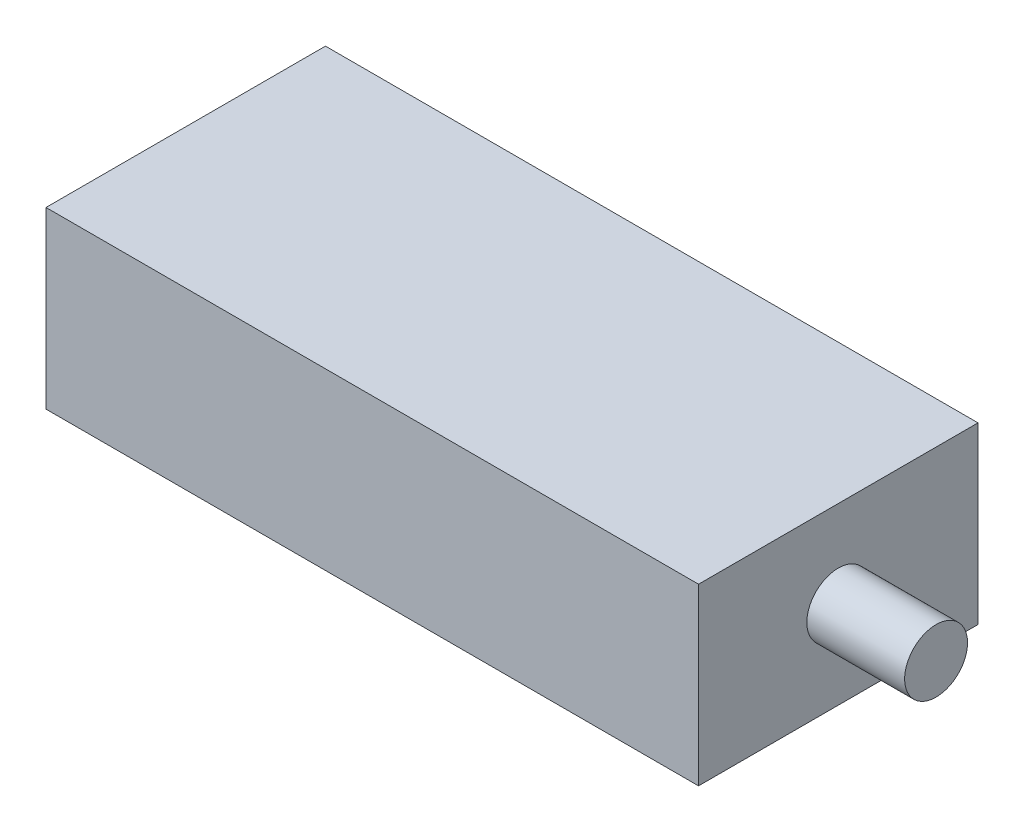
SolidWorks part; units mm, degrees
ref_plane "Front Plane" through (0, 0, 0) normal (0, 0, 1) x (1, 0, 0)
ref_plane "Top Plane" through (0, 0, 0) normal (0, 1, 0) x (1, 0, 0)
ref_plane "Right Plane" through (0, 0, 0) normal (1, 0, 0) x (0, 0, -1)
sketch "Sketch1" plane through (0, 0, 0) normal (0, 1, 0) x (1, 0, 0)
  line L1 (-59.309, -25.4) -> (59.309, -25.4)
  line L2 (-59.309, -25.4) -> (-59.309, 25.4)
  line L3 (-59.309, 25.4) -> (59.309, 25.4)
  line L4 (59.309, -25.4) -> (59.309, 25.4)
  line L5 (-59.309, -25.4) -> (59.309, 25.4) construction
  line L6 (-59.309, 25.4) -> (59.309, -25.4) construction
  point P0 (0, 0)
  dimension "D1" = 118.618
  dimension "D2" = 50.8
extrude "Boss-Extrude1" add sketch "Sketch1" along normal blind 31.75
sketch "Sketch2" plane through (59.309, 0, 0) normal (1, 0, 0) x (0, 0, -1)
  line L0 (-25.4, 31.75) -> (-25.4, 0) construction
  circle A0 centre (0, 15.875) radius 5.715
  point P10 (-25.4, 15.875)
  dimension "D1" = 11.43
extrude "Boss-Extrude2" add sketch "Sketch2" along normal blind 17.78
sketch "Sketch3" plane through (-59.309, 0, 0) normal (-1, 0, 0) x (0, 0, 1)
  line L1 (-7.964, 11.6586) -> (-2.54, 11.6586)
  line L3 (-7.964, 20.0914) -> (-2.54, 20.0914)
  line L5 (-2.54, 11.6586) -> (0, 14.1986)
  line L6 (0, 14.1986) -> (0, 11.6586) construction
  line L8 (-2.54, 20.0914) -> (0, 17.5514)
  line L9 (0, 17.5514) -> (0, 20.0914) construction
  line L11 (0, 0) -> (0, 41.1546) construction
  line L14 (2.54, 20.0914) -> (0, 17.5514)
  line L15 (2.54, 11.6586) -> (0, 14.1986)
  line L16 (7.964, 20.0914) -> (2.54, 20.0914)
  line L18 (7.964, 11.6586) -> (2.54, 11.6586)
  arc A0 (-7.964, 11.6586) -> (-7.964, 20.0914) centre (-5.1305, 15.875) cw
  arc A1 (7.964, 11.6586) -> (7.964, 20.0914) centre (5.1305, 15.875) ccw
  point P7 (0, 0)
  dimension "D6" = 5.08
  dimension "D1" = 8.4328
  dimension "D2" = 5.424
  dimension "D3" = 2.54
  dimension "D4" = 45
  dimension "D5" = 2.54
extrude "Cut-Extrude1" cut sketch "Sketch3" against normal blind 9.906
